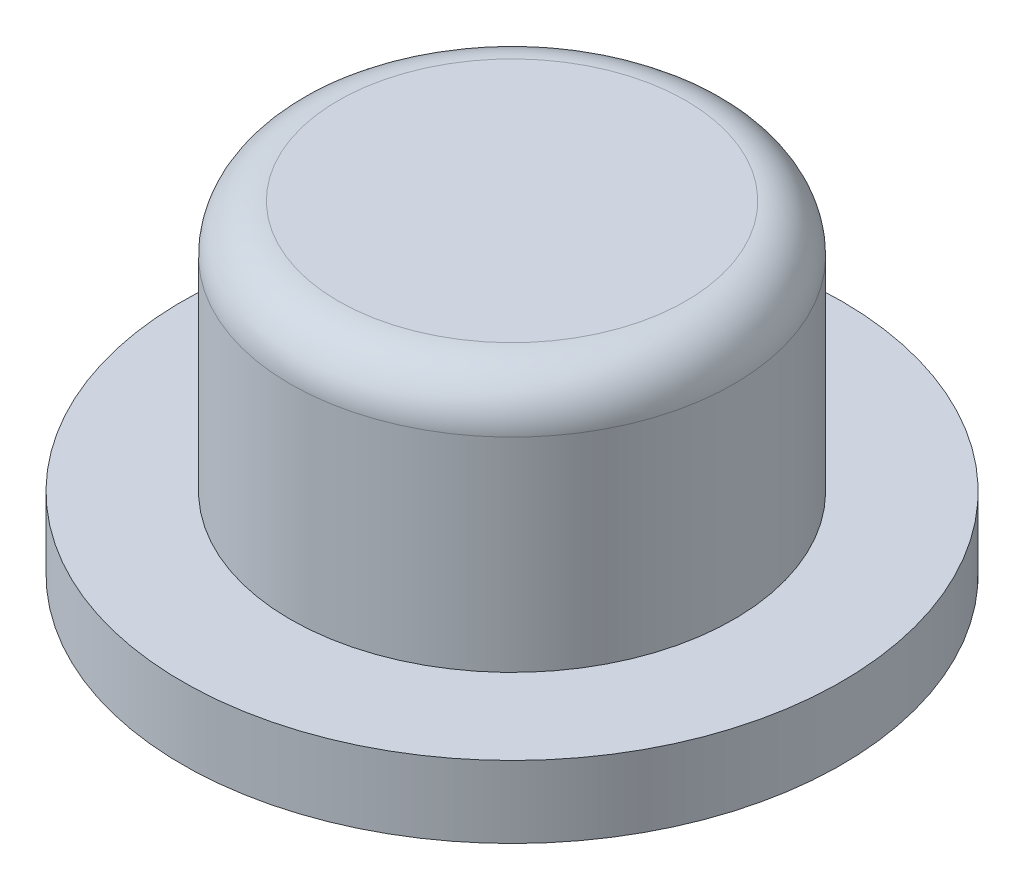
SolidWorks part; units mm, degrees
ref_plane "Face" through (0, 0, 0) normal (0, 0, 1) x (1, 0, 0)
ref_plane "Dessus" through (0, 0, 0) normal (0, 1, 0) x (1, 0, 0)
ref_plane "Droite" through (0, 0, 0) normal (1, 0, 0) x (0, 0, -1)
sketch "Sketch1" plane through (0, 0, 0) normal (0, 1, 0) x (1, 0, 0)
  circle A0 centre (0, 0) radius 3.4925
  dimension "D1" = 6.985
extrude "Boss-Extrude1" add sketch "Sketch1" along normal blind 0.762
sketch "Sketch2" plane through (0, 0.762, 0) normal (0, 1, 0) x (1, 0, 0)
  circle A0 centre (0, 0) radius 2.3495
  dimension "D1" = 4.699
extrude "Boss-Extrude2" add sketch "Sketch2" along normal blind 2.667
fillet "Fillet1" radius 0.508 1 edges at (0, 3.429, 2.3495)
